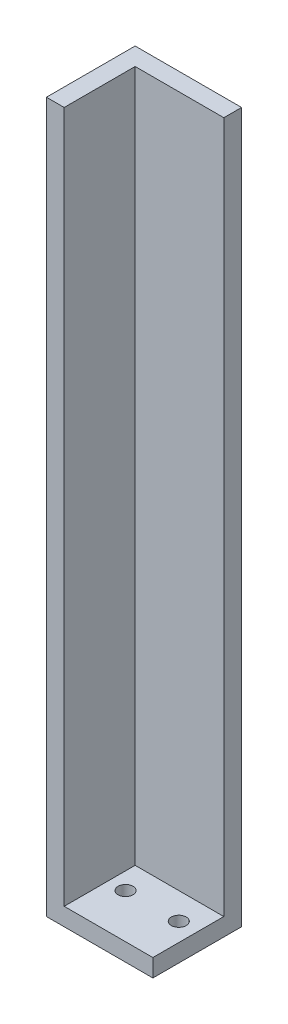
SolidWorks part; units mm, degrees
ref_plane "Front Plane" through (0, 0, 0) normal (0, 0, 1) x (1, 0, 0)
ref_plane "Top Plane" through (0, 0, 0) normal (0, 1, 0) x (1, 0, 0)
ref_plane "Right Plane" through (0, 0, 0) normal (1, 0, 0) x (0, 0, -1)
sketch "Sketch1" plane through (0, 0, 0) normal (0, 1, 0) x (1, 0, 0)
  line L1 (30, -25) -> (-30, -25)
  line L2 (30, -25) -> (30, 25)
  line L3 (30, 25) -> (-30, 25)
  line L4 (-30, -25) -> (-30, 25)
  line L5 (30, -25) -> (-30, 25) construction
  line L6 (30, 25) -> (-30, -25) construction
  point P0 (0, 0)
  dimension "D1" = 60
  dimension "D2" = 50
extrude "Boss-Extrude1" add sketch "Sketch1" along normal mid plane 400 contours L3 L4 L1 L2
sketch "Sketch2" plane through (30, 0, 0) normal (1, 0, 0) x (0, 0, -1)
  line L0 (-25, -200) -> (25, -200) construction
  line L1 (-25, 200) -> (15, 200)
  line L2 (-25, 200) -> (-25, -190)
  line L3 (-25, -190) -> (15, -190)
  line L4 (15, 200) -> (15, -190)
  line L5 (25, 200) -> (25, -200) construction
  dimension "D1" = 10
  dimension "D2" = 10
extrude "Cut-Extrude1" cut sketch "Sketch2" against normal offset from surface (50 mm away) 10 up to face at (-30, 0, 0)
sketch "Sketch4" plane through (0, -200, 0) normal (0, -1, 0) x (1, 0, 0)
  circle A0 centre (-10.4, 0) radius 4.2
  circle A1 centre (19.6, 0) radius 4.2
  dimension "D1" = 8.4
extrude "Cut-Extrude3" cut sketch "Sketch4" against normal through all
